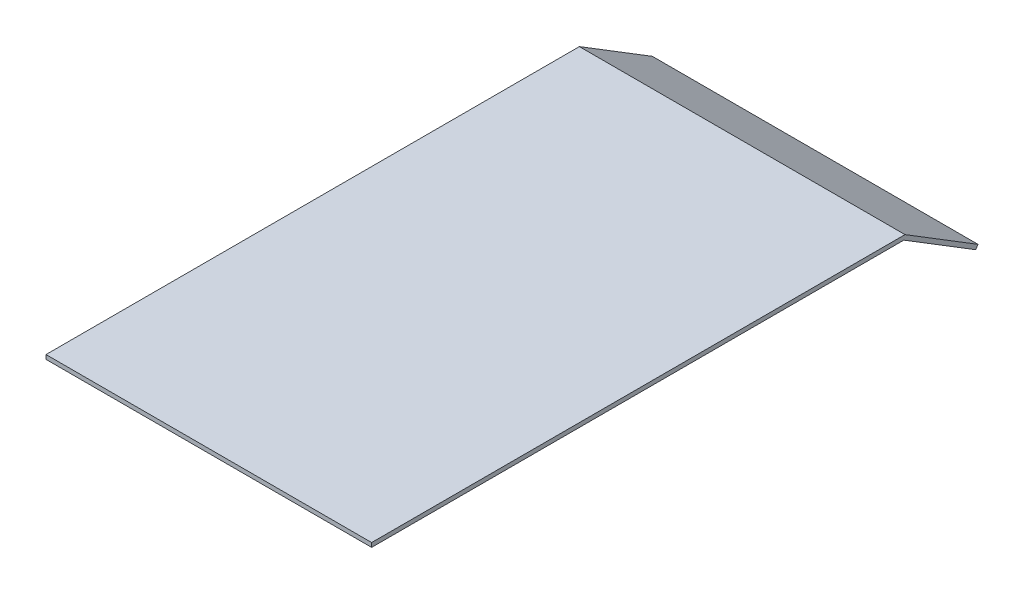
SolidWorks part; units mm, degrees
ref_plane "Front Plane" through (0, 0, 0) normal (0, 0, 1) x (1, 0, 0)
ref_plane "Top Plane" through (0, 0, 0) normal (0, 1, 0) x (1, 0, 0)
ref_plane "Right Plane" through (0, 0, 0) normal (1, 0, 0) x (0, 0, -1)
sketch "Sketch1" plane through (0, 0, 0) normal (0, 1, 0) x (1, 0, 0)
  line L1 (-116, 190) -> (116, 190)
  line L2 (-116, 190) -> (-116, -190)
  line L3 (-116, -190) -> (116, -190)
  line L4 (116, 190) -> (116, -190)
  line L5 (-116, 190) -> (116, -190) construction
  line L6 (-116, -190) -> (116, 190) construction
  point P0 (0, 0)
  dimension "D1" = 380
  dimension "D2" = 232
extrude "Boss-Extrude1" add sketch "Sketch1" along normal blind 3
sketch "Sketch5" plane through (116, 0, 0) normal (1, 0, 0) x (0, 0, -1)
  line L3 (190, 3) -> (242, -29)
extrude "Extrude-Thin1" add sketch "Sketch5" against normal blind 232 thin contours L3
